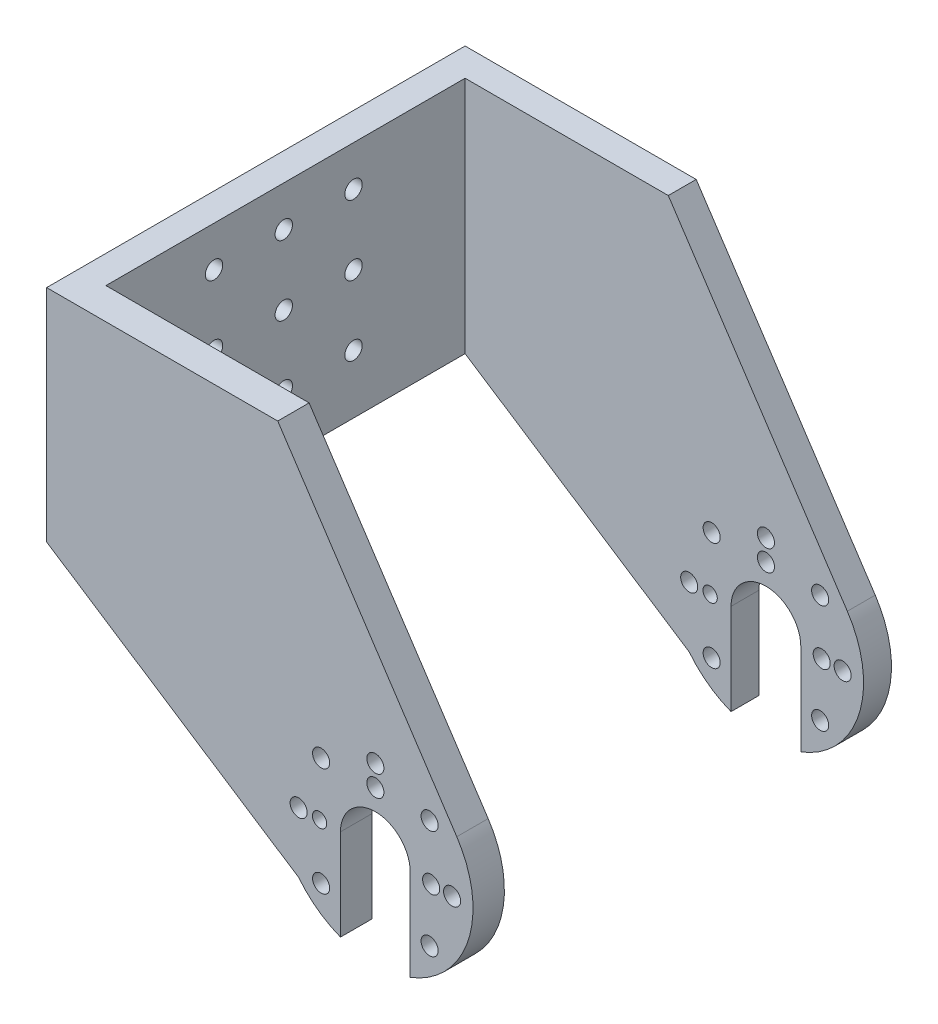
SolidWorks part; units mm, degrees
ref_plane "정면" through (0, 0, 0) normal (0, 0, 1) x (1, 0, 0)
ref_plane "윗면" through (0, 0, 0) normal (0, 1, 0) x (1, 0, 0)
ref_plane "우측면" through (0, 0, 0) normal (1, 0, 0) x (0, 0, -1)
sketch "스케치1" plane through (0, 0, 0) normal (0, 0, 1) x (1, 0, 0)
  line L0 (11.674, 7.7277) -> (-14, 46.5127)
  line L4 (-14, 46.5127) -> (-47.1329, 46.5127)
  line L5 (-11, -8.6603) -> (-47.1329, 14.9217)
  line L8 (-47.1329, 46.5127) -> (-47.1329, 14.9217)
  circle A18 centre (0, 0) radius 5
  circle A19 centre (0, 8) radius 1.225
  circle A20 centre (0, 11) radius 1.225
  arc A21 (-11, -8.6603) -> (11.674, 7.7277) centre (0, 0) ccw
  circle A22 centre (7.7782, 7.7782) radius 1.225
  circle A23 centre (8, 0) radius 1.225
  circle A24 centre (11, 0) radius 1.225
  circle A25 centre (7.7782, -7.7782) radius 1.225
  circle A26 centre (0, -8) radius 1.225
  circle A27 centre (0, -11) radius 1.225
  circle A28 centre (-7.7782, -7.7782) radius 1.225
  circle A29 centre (-8, 0) radius 1.025
  circle A30 centre (-11, 0) radius 1.225
  circle A31 centre (-7.7782, 7.7782) radius 1.225
  dimension "D1" = 10
  dimension "D3" = 2.45
  dimension "D5" = 28
  dimension "D6" = 2.05
  dimension "D2" = 8
  dimension "D4" = 11
  dimension "D7" = 7.7782
  dimension "D8" = 8
  dimension "D9" = 11
  dimension "D10" = 11.674
  dimension "D11" = 7.7782
  dimension "D12" = 8
  dimension "D13" = 14
  dimension "D14" = 47.1329
  dimension "D15" = 7.7782
  dimension "D16" = 11
  dimension "D17" = 14.9217
  dimension "D18" = 7.7782
  dimension "D19" = 8
  dimension "D20" = 11
extrude "보스-돌출1" add sketch "스케치1" along normal blind 60
sketch "스케치2" plane through (0, 46.5127, 0) normal (0, 1, 0) x (1, 0, 0)
  line L0 (-43.1329, -4) -> (14, -4)
  line L1 (14, -60) -> (14, 0) construction
  line L2 (14, -4) -> (14, -55.5)
  line L3 (14, -55.5) -> (-43.1329, -55.5)
  line L4 (-43.1329, -55.5) -> (-43.1329, -4)
  line L5 (-14, 0) -> (-47.1329, 0) construction
  line L6 (-47.1329, -60) -> (-47.1329, 0) construction
  point P4 (-30.5665, 0)
  dimension "D1" = 4
  dimension "D2" = 51.5
  dimension "D3" = 4
extrude "컷-돌출1" cut sketch "스케치2" against normal blind 66
sketch "스케치4" plane through (0, 0, 60) normal (0, 0, 1) x (1, 0, 0)
  line L0 (0, 5) -> (0, -5) construction
  line L1 (5, 0) -> (-5, 0) construction
  line L2 (-5, 0) -> (-5, -13.0767)
  line L3 (5, 0) -> (5, -13.0767)
  line L4 (-5, 0) -> (5, 0)
  circle A0 centre (0, 0) radius 5 construction
  arc A1 (-11, -8.6603) -> (11.674, 7.7277) centre (0, 0) ccw construction
  arc A2 (-5, -13.0767) -> (5, -13.0767) centre (0, 0) ccw
extrude "컷-돌출3" cut sketch "스케치4" against normal blind 60.339
sketch "스케치6" plane through (-47.1329, 0, 0) normal (-1, 0, 0) x (0, 0, 1)
  line L0 (30, 46.5127) -> (30, 14.9217) construction
  line L1 (60, 46.5127) -> (0, 46.5127) construction
  line L2 (60, 14.9217) -> (0, 14.9217) construction
  line L3 (0, 30.7172) -> (60, 30.7172) construction
  line L4 (0, 46.5127) -> (0, 14.9217) construction
  line L5 (60, 46.5127) -> (60, 14.9217) construction
  line L6 (30, 30.7172) -> (40, 30.7172) construction
  line L7 (30, 30.7172) -> (20, 30.7172) construction
  circle A0 centre (30, 30.7172) radius 1.25
  circle A1 centre (40, 30.7172) radius 1.25
  circle A2 centre (20, 30.7172) radius 1.25
  circle A3 centre (20, 40.7172) radius 1.25
  circle A4 centre (30, 40.7172) radius 1.25
  circle A5 centre (40, 40.7172) radius 1.25
  circle A6 centre (20, 20.7172) radius 1.25
  circle A7 centre (30, 20.7172) radius 1.25
  circle A8 centre (40, 20.7172) radius 1.25
  dimension "D1" = 2.5
  dimension "D3" = 10
  dimension "D5" = 10
  dimension "D8" = 5.7955
  dimension "D9" = 5.7955
  dimension "D2" = 2
  dimension "D4" = 2
  dimension "D6" = 2
  dimension "D7" = 2
extrude "컷-돌출4" cut sketch "스케치6" against normal blind 10
